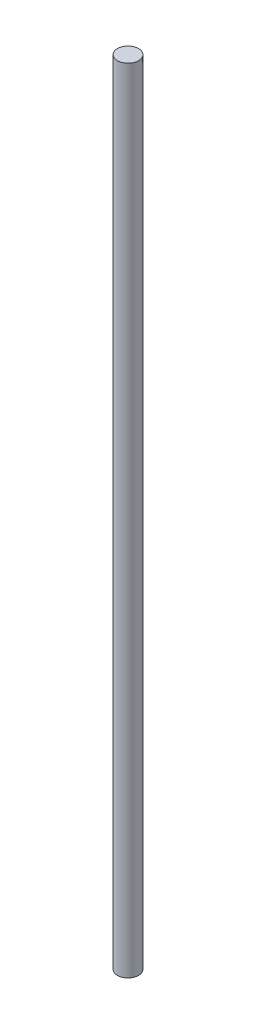
SolidWorks part; units mm, degrees
ref_plane "Front Plane" through (0, 0, 0) normal (0, 0, 1) x (1, 0, 0)
ref_plane "Top Plane" through (0, 0, 0) normal (0, 1, 0) x (1, 0, 0)
ref_plane "Right Plane" through (0, 0, 0) normal (1, 0, 0) x (0, 0, -1)
sketch "Sketch1" plane through (0, 0, 0) normal (0, 1, 0) x (1, 0, 0)
  circle A0 centre (-4.9111, 2.4555) radius 1.9844
  dimension "D1" = 3.9688
extrude "Boss-Extrude1" add sketch "Sketch1" along normal blind 149.225
